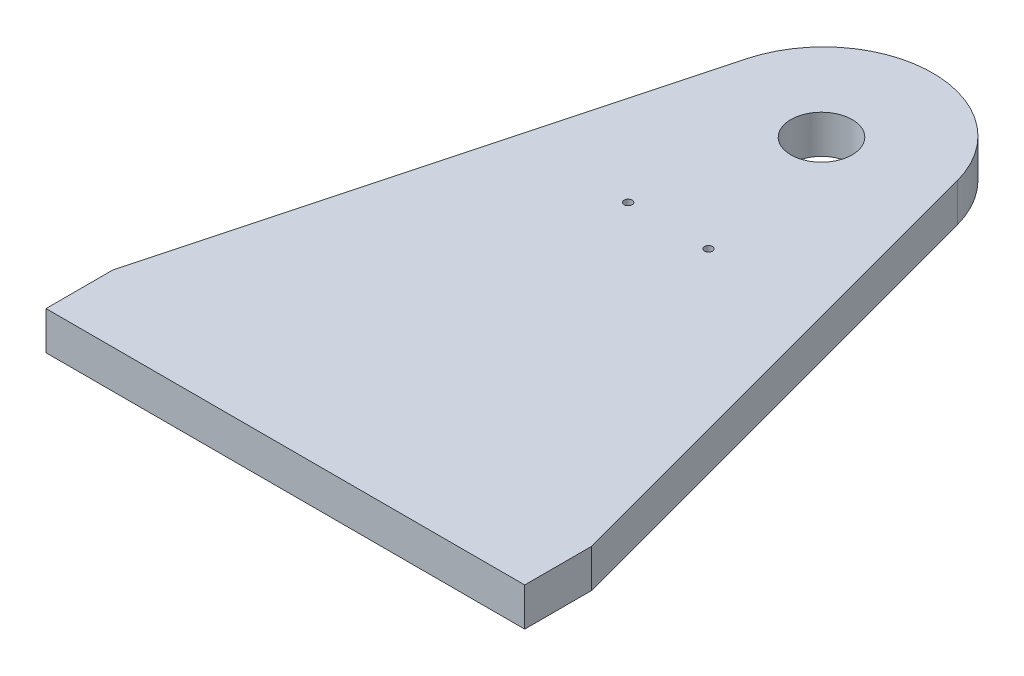
SolidWorks part; units mm, degrees
material "PTFE (general)"
ref_plane "Front Plane" through (0, 0, 0) normal (0, 0, 1) x (1, 0, 0)
ref_plane "Top Plane" through (0, 0, 0) normal (0, 1, 0) x (1, 0, 0)
ref_plane "Right Plane" through (0, 0, 0) normal (1, 0, 0) x (0, 0, -1)
sketch "Sketch1" plane through (0, 0, 0) normal (0, 1, 0) x (1, 0, 0)
  line L0 (-55.1189, 295.8) -> (-125, 35)
  line L1 (-125, 35) -> (-125, 0)
  line L2 (-125, 0) -> (125, 0)
  line L3 (125, 0) -> (125, 35)
  line L5 (125, 35) -> (55.1189, 295.8)
  arc A0 (-55.1189, 295.8) -> (55.1189, 295.8) centre (0, 281.0309) cw
  point P2 (0, 0)
  point P8 (0, 0)
  dimension "D1" = 35
  dimension "D2" = 250
  dimension "D3" = 195
  dimension "D4" = 270
  dimension "D5" = 195
  dimension "D6" = 270
extrude "Boss-Extrude1" add sketch "Sketch1" along normal blind 20
sketch "Sketch3" plane through (0, 20, 0) normal (0, 1, 0) x (1, 0, 0)
  line L0 (0, 0) -> (0, 338.0942) construction
  line L1 (-50.4531, 200) -> (50.0066, 200) construction
  line L3 (-125, 0) -> (125, 0) construction
  arc A0 (55.1189, 295.8) -> (-55.1189, 295.8) centre (0, 281.0309) ccw construction
  circle A1 centre (-21, 200) radius 2.1
  circle A2 centre (21, 200) radius 2.1
  circle A3 centre (0, 280) radius 16
  dimension "D2" = 4.2
  dimension "D4" = 32
  dimension "D1" = 280
  dimension "D3" = 21
  dimension "D5" = 80
extrude "Cut-Extrude2" cut sketch "Sketch3" against normal up to surface (20 mm away) up to face at (0, 0, -117.3157)
